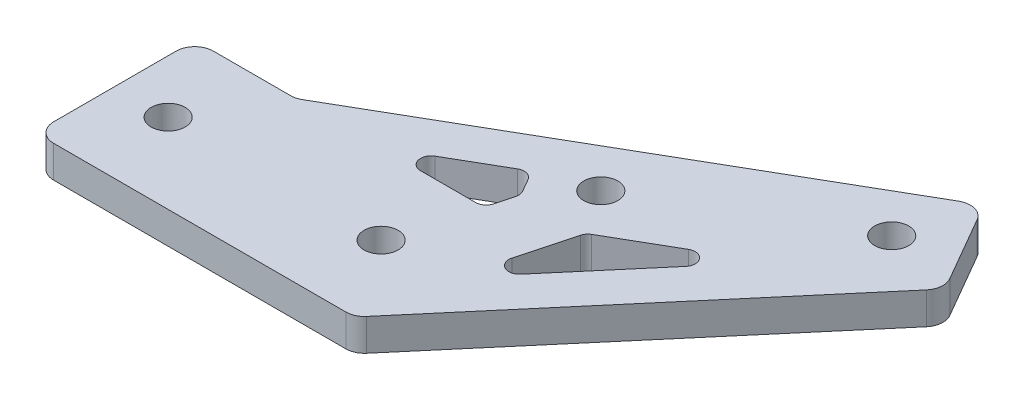
SolidWorks part; units mm, degrees
ref_plane "正面" through (0, 0, 0) normal (0, 0, 1) x (1, 0, 0)
ref_plane "平面" through (0, 0, 0) normal (0, 1, 0) x (1, 0, 0)
ref_plane "右側面" through (0, 0, 0) normal (1, 0, 0) x (0, 0, -1)
sketch "ｽｹｯﾁ1" plane through (0, 0, 0) normal (0, 1, 0) x (1, 0, 0)
  line L0 (164.476, -13.1178) -> (164.476, 1.8822) construction
  line L1 (164.476, 1.8822) -> (-55.524, 1.8822) construction
  line L3 (-55.524, -13.1178) -> (164.476, -13.1178) construction
  line L4 (26.6854, 10.5425) -> (31.6854, 1.8822) construction
  line L5 (31.6854, 1.8822) -> (334.7943, 176.8822) construction
  line L6 (334.7943, 176.8822) -> (329.7943, 185.5425) construction
  line L7 (329.7943, 185.5425) -> (26.6854, 10.5425) construction
  line L8 (164.476, -13.1178) -> (164.476, 1.8822) construction
  line L9 (164.476, 1.8822) -> (-55.524, 1.8822) construction
  line L11 (-55.524, -13.1178) -> (164.476, -13.1178) construction
  line L12 (26.6854, 10.5425) -> (31.6854, 1.8822) construction
  line L13 (31.6854, 1.8822) -> (334.7943, 176.8822) construction
  line L14 (334.7943, 176.8822) -> (329.7943, 185.5425) construction
  line L15 (329.7943, 185.5425) -> (26.6854, 10.5425) construction
  line L16 (29.47, 0) -> (419.1814, 225) construction
  line L17 (0, 0) -> (220, 0) construction
  line L18 (0, 0) -> (0, -15) construction
  line L19 (0, -15) -> (220, -15) construction
  line L20 (220, 0) -> (220, -15) construction
  line L21 (419.1814, 225) -> (414.1814, 233.6603) construction
  line L22 (414.1814, 233.6603) -> (24.47, 8.6603) construction
  line L23 (24.47, 8.6603) -> (29.47, 0) construction
  dimension "D1" = 15
  dimension "D2" = 220
  dimension "D3" = 29.47
  dimension "D4" = 30
  dimension "D5" = 450
  dimension "D6" = 10
sketch "ｽｹｯﾁ2" plane through (0, 0, 0) normal (0, 1, 0) x (1, 0, 0)
  line L0 (29.47, 0) -> (419.1814, 225) construction
  line L1 (24.47, 8.6603) -> (29.47, 0) construction
  line L2 (414.1814, 233.6603) -> (24.47, 8.6603) construction
  line L3 (220, 0) -> (220, -15) construction
  line L4 (0, -15) -> (220, -15) construction
  line L6 (0, 0) -> (220, 0) construction
  line L7 (29.47, 0) -> (419.1814, 225) construction
  line L8 (24.47, 8.6603) -> (29.47, 0) construction
  line L9 (414.1814, 233.6603) -> (24.47, 8.6603) construction
  line L10 (220, 0) -> (220, -15) construction
  line L11 (0, -15) -> (220, -15) construction
  line L13 (0, 0) -> (220, 0) construction
  line L14 (26.97, 4.3301) -> (48.6206, 16.8301) construction
  line L15 (0, -7.5) -> (25, -7.5) construction
  line L16 (24.47, 8.6603) -> (9.47, 0)
  line L18 (24.47, 8.6603) -> (50.4508, 23.6603)
  line L19 (50.4508, 23.6603) -> (55.4508, 15)
  line L20 (55.4508, 15) -> (30, -15)
  line L21 (30, -15) -> (0, -15)
  line L22 (0, -15) -> (0, 0)
  line L23 (0, 0) -> (9.47, 0)
  circle A0 centre (48.6206, 16.8301) radius 1.6
  circle A1 centre (25, -7.5) radius 1.6
  circle A2 centre (31.3001, 6.8301) radius 1.6
  circle A3 centre (5, -7.5) radius 1.6
  point P24 (0, -7.5)
  dimension "D3" = 3.2
  dimension "D4" = 3.2
  dimension "D5" = 3.2
  dimension "D6" = 3.2
  dimension "D1" = 25
  dimension "D2" = 25
  dimension "D7" = 5
  dimension "D8" = 5
  dimension "D9" = 5
  dimension "D10" = 5
extrude "ﾎﾞｽ - 押し出し1" add sketch "ｽｹｯﾁ2" along normal mid plane 3
sketch "ｽｹｯﾁ3" plane through (0, 1.5, 0) normal (0, 1, 0) x (1, 0, 0)
  line L0 (0, -15) -> (220, -15) construction
  line L1 (0, 0) -> (220, 0) construction
  line L2 (414.1814, 233.6603) -> (24.47, 8.6603) construction
  line L3 (24.47, 8.6603) -> (29.47, 0) construction
  line L4 (29.47, 0) -> (419.1814, 225) construction
  line L5 (0, -15) -> (220, -15)
  line L6 (0, 0) -> (220, 0)
  line L7 (414.1814, 233.6603) -> (24.47, 8.6603)
  line L8 (24.47, 8.6603) -> (29.47, 0)
  line L9 (29.47, 0) -> (419.1814, 225)
  line L10 (48.9867, 18.1962) -> (12.3252, -2.9704)
  line L11 (12.3252, -2.9704) -> (7.2558, -11)
  line L12 (7.2558, -11) -> (28.1479, -11)
  line L13 (28.1479, -11) -> (50.5782, 15.4396)
  line L14 (50.5782, 15.4396) -> (48.9867, 18.1962)
  line L15 (50.4508, 23.6603) -> (9.47, 0)
  line L16 (9.47, 0) -> (0, 0)
  line L17 (0, -15) -> (30, -15)
  line L18 (30, -15) -> (55.4508, 15)
  line L19 (55.4508, 15) -> (50.4508, 23.6603)
  line L20 (50.4508, 23.6603) -> (9.47, 0)
  line L22 (0, -15) -> (30, -15)
  line L23 (30, -15) -> (55.4508, 15)
  line L24 (55.4508, 15) -> (50.4508, 23.6603)
  line L25 (27.879, 2.7557) -> (27.1406, 0)
  line L26 (34.0628, 2.6517) -> (33.3523, 0)
  line L27 (0, -10.2338) -> (25, -7.5) construction
  line L28 (52.9508, 19.3301) -> (31.3001, 6.8301) construction
  line L29 (15.8097, 3.6603) -> (40.2703, -2.8939) construction
  line L30 (34.0628, 2.6517) -> (31.4468, -7.1115)
  line L37 (9.47, 0) -> (0, -15) construction
  line L38 (9.47, 0) -> (0, 0)
  line L39 (0, 0) -> (0, -15)
  line L40 (0, 0) -> (0, -15)
  dimension "D3" = 15
  dimension "D4" = 6
  dimension "D5" = 3.75
  dimension "D1" = 0
  dimension "D2" = 4
extrude "ｶｯﾄ - 押し出し1" cut sketch "ｽｹｯﾁ3" against normal blind 3 contours L25 L8 L10 L6 | L9 L26 L6 L13 | L6 L30 L13
fillet "ﾌｨﾚｯﾄ1" radius 1 7 edges at (45.1695, 0, -9.0641) (17.47, 0, 0) (26.47, 0, -5.1962) (27.879, 0, -2.7557) (27.1406, 0, 0) (31.4468, 0, 7.1115) (34.0628, 0, -2.6517)
fillet "ﾌｨﾚｯﾄ2" radius 1.75 6 edges at (50.4508, 0, -23.6603) (55.4508, 0, -15) (30, 0, 15) (9.47, 0, 0) (0, 0, 0) (0, 0, 15)
sketch "ｽｹｯﾁ4" plane through (0, -1.5, 0) normal (0, -1, 0) x (1, 0, 0)
  line L0 (50.4508, -23.6603) -> (55.4508, -15) construction
  line L1 (24.47, -8.6603) -> (50.4508, -23.6603) construction
  line L2 (24.47, -8.6603) -> (29.47, 0) construction
  line L3 (29.47, 0) -> (419.1814, -225) construction
  line L4 (55.4508, -15) -> (30, 15) construction
  line L5 (0, 0) -> (220, 0) construction
  line L6 (30, 15) -> (0, 15) construction
  line L7 (0, 15) -> (0, 0) construction
  line L8 (50.4508, -23.6603) -> (55.4508, -15)
  line L9 (24.47, -8.6603) -> (50.4508, -23.6603)
  line L10 (24.47, -8.6603) -> (29.47, 0)
  line L11 (29.47, 0) -> (419.1814, -225)
  line L12 (55.4508, -15) -> (30, 15)
  line L13 (0, 0) -> (220, 0)
  line L14 (30, 15) -> (0, 15)
  line L15 (0, 15) -> (0, 0)
  circle A0 centre (29.47, 0) radius 1
  dimension "D1" = 2
